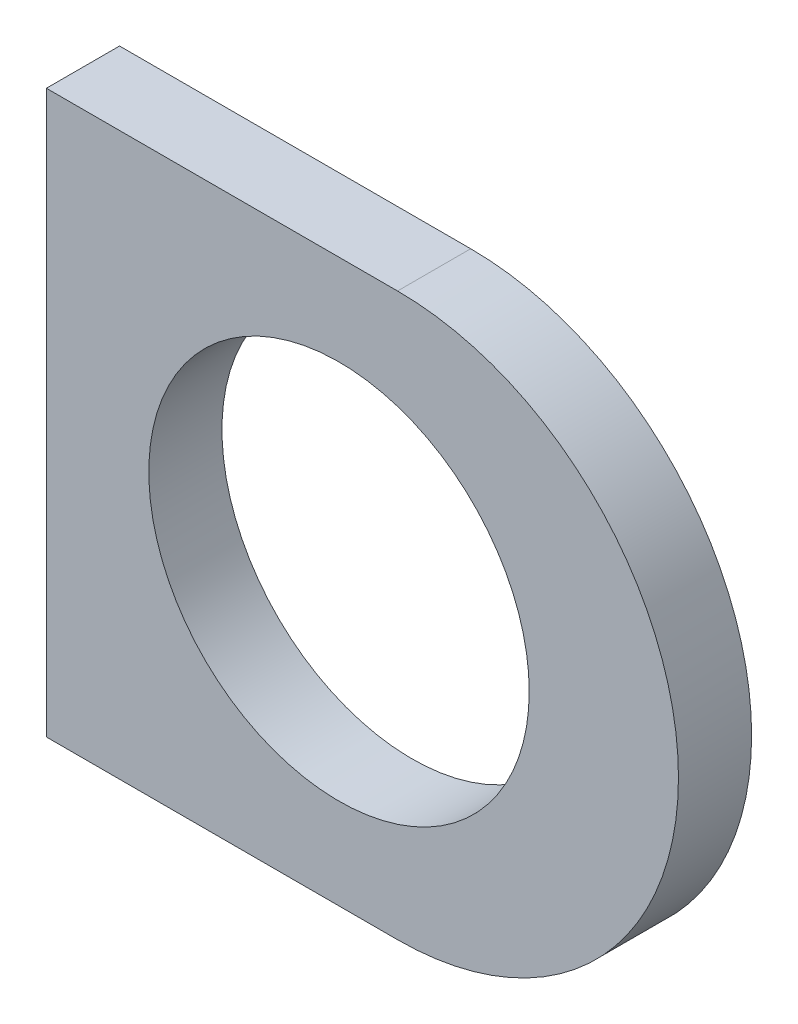
SolidWorks part; units mm, degrees
ref_plane "Front Plane" through (0, 0, 0) normal (0, 0, 1) x (1, 0, 0)
ref_plane "Top Plane" through (0, 0, 0) normal (0, 1, 0) x (1, 0, 0)
ref_plane "Right Plane" through (0, 0, 0) normal (1, 0, 0) x (0, 0, -1)
sketch "Sketch1" plane through (0, 0, 0) normal (0, 0, 1) x (1, 0, 0)
  line L0 (-60, 48) -> (-60, -48)
  line L3 (-60, 48) -> (0, 48)
  line L4 (-60, -48) -> (0, -48)
  arc A1 (0, -48) -> (0, 48) centre (0, 0) ccw
extrude "Boss-Extrude1" add sketch "Sketch1" along normal blind 12.5
sketch "Sketch2" plane through (0, 0, 0) normal (0, 0, 1) x (1, 0, 0)
  circle A0 centre (-10, 0) radius 32.5
extrude "Cut-Extrude1" cut sketch "Sketch2" against normal through all and the other way through all
